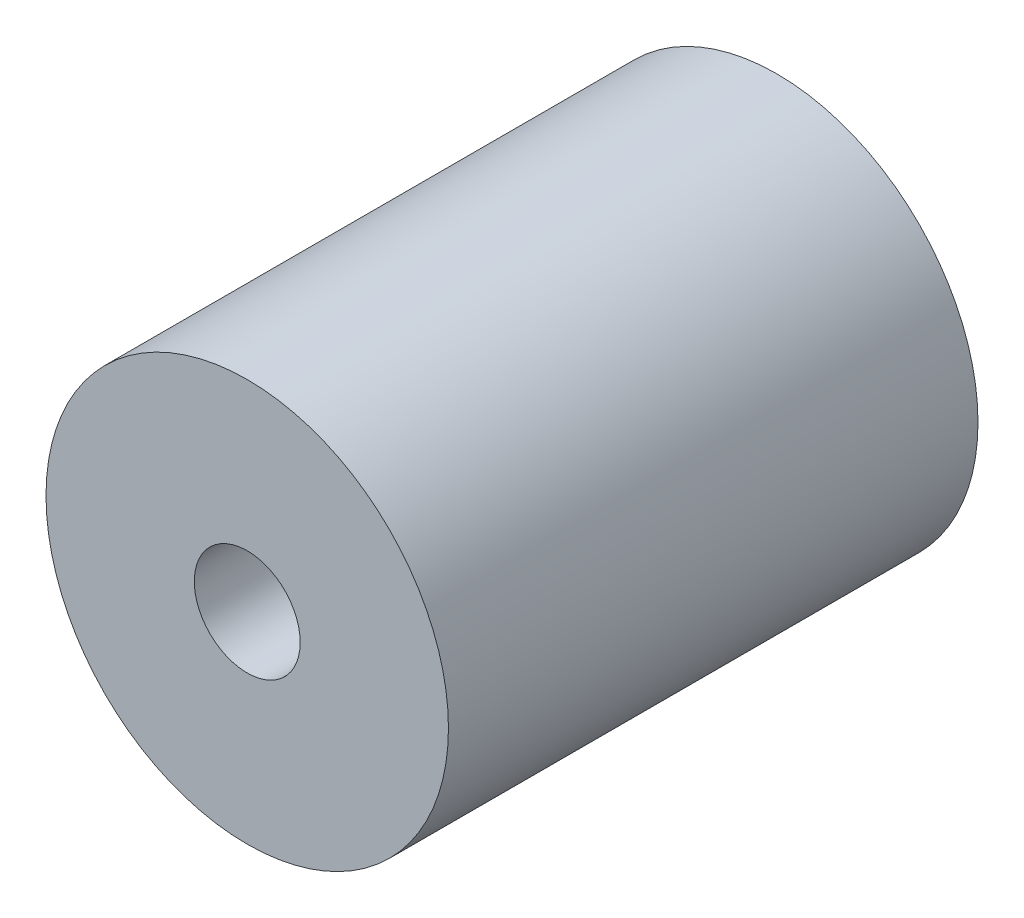
SolidWorks part; units mm, degrees
ref_plane "前视基准面" through (0, 0, 0) normal (0, 0, 1) x (1, 0, 0)
ref_plane "上视基准面" through (0, 0, 0) normal (0, 1, 0) x (1, 0, 0)
ref_plane "右视基准面" through (0, 0, 0) normal (1, 0, 0) x (0, 0, -1)
other "Configuration Table"
sketch "草图1" plane through (0, 0, 0) normal (0, 0, 1) x (1, 0, 0)
  circle A0 centre (0, 0) radius 9.5
  dimension "D1" = 19
extrude "凸台-拉伸1" add sketch "草图1" along normal blind 25 contours A0
sketch "草图2" plane through (0, 0, 0) normal (0, 0, -1) x (-1, 0, 0)
  circle A0 centre (0, 0) radius 4
  dimension "D1" = 8
extrude "切除-拉伸1" cut sketch "草图2" against normal blind 17.5
sketch "草图3" plane through (0, 0, 25) normal (0, 0, 1) x (1, 0, 0)
  circle A0 centre (0, 0) radius 2.5
  dimension "D1" = 5
extrude "切除-拉伸2" cut sketch "草图3" against normal blind 7.5
